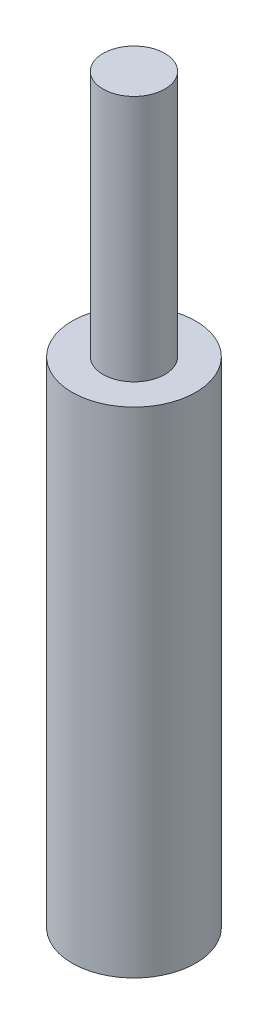
SolidWorks part; units mm, degrees
ref_plane "Front Plane" through (0, 0, 0) normal (0, 0, 1) x (1, 0, 0)
ref_plane "Top Plane" through (0, 0, 0) normal (0, 1, 0) x (1, 0, 0)
ref_plane "Right Plane" through (0, 0, 0) normal (1, 0, 0) x (0, 0, -1)
sketch "Sketch1" plane through (0, 0, 0) normal (0, 1, 0) x (1, 0, 0)
  circle A0 centre (0, 0) radius 3.175
  dimension "D1" = 6.35
extrude "Boss-Extrude1" add sketch "Sketch1" along normal blind 25.4
sketch "Sketch2" plane through (0, 25.4, 0) normal (0, 1, 0) x (1, 0, 0)
  circle A0 centre (0, 0) radius 1.5875
  dimension "D1" = 3.175
extrude "Boss-Extrude2" add sketch "Sketch2" along normal blind 12.7 contours A0
sketch "Sketch4" plane through (0, 0, 0) normal (0, -1, 0) x (1, 0, 0)
  line L0 (-3.175, 0) -> (3.175, 0) construction
  line L1 (0, 3.175) -> (0, -3.175) construction
  circle A0 centre (0, 0) radius 3.175 construction
  point P9 (0, 0)
hole_wizard "1/8 (0.125) Diameter Hole1" positions "Sketch4" profile "Sketch5" hole size "1/8" standard "ANSI Inch"
sketch "Sketch5" plane through (0, 0, 0) normal (1, 0, 0) x (0, 0, -1)
  line L0 (0, 0) -> (0, 13.6539)
  line L1 (0, 13.6539) -> (1.5875, 12.7)
  line L2 (1.5875, 12.7) -> (1.5875, 0)
  line L5 (1.5875, 0) -> (0, 0)
  line L10 (0, 13.6539) -> (-1.5875, 12.7) construction
  line L11 (0, -6.35) -> (0, 107.95) construction
  dimension "Hole Dia." = 3.175
  dimension "Hole Depth" = 12.7
  dimension "Drill Angle" = 118
